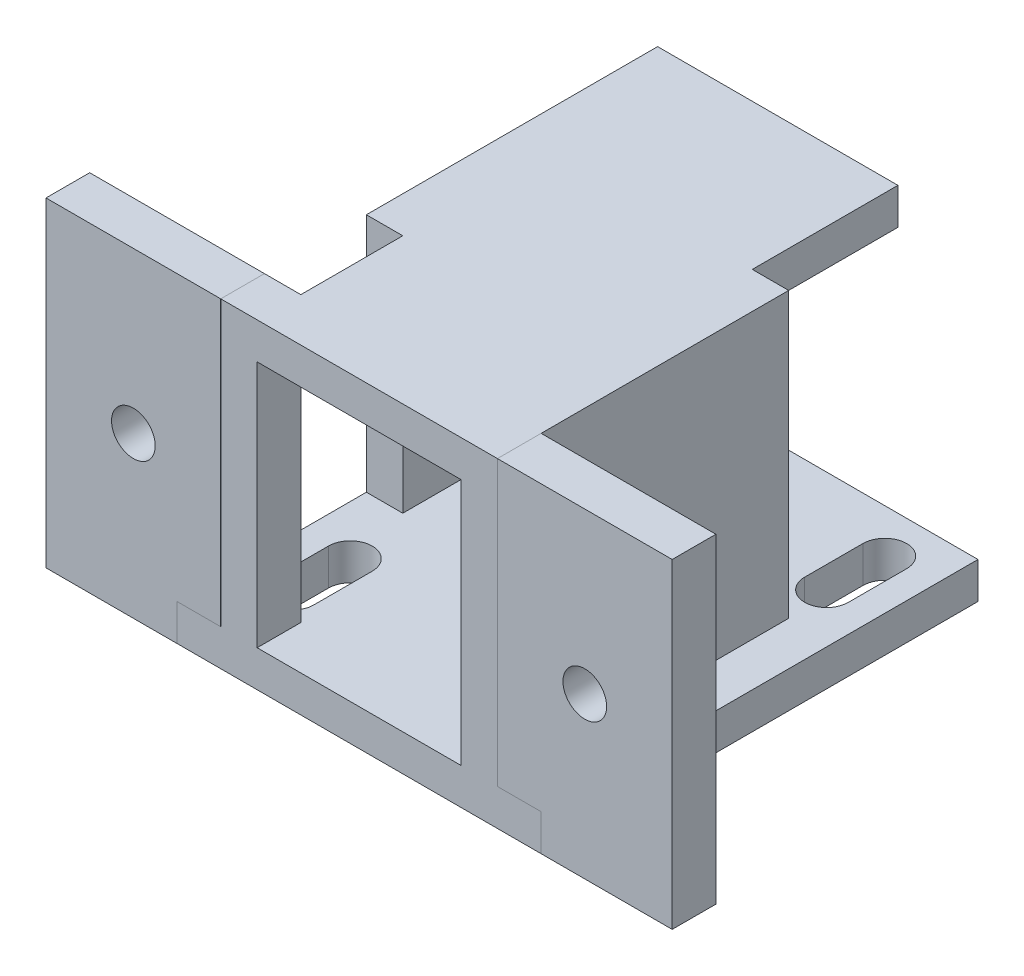
SolidWorks part; units mm, degrees
ref_plane "Front Plane" through (0, 0, 0) normal (0, 0, 1) x (1, 0, 0)
ref_plane "Top Plane" through (0, 0, 0) normal (0, 1, 0) x (1, 0, 0)
ref_plane "Right Plane" through (0, 0, 0) normal (1, 0, 0) x (0, 0, -1)
sketch "Sketch1" plane through (0, 0, 0) normal (0, 0, 1) x (1, 0, 0)
  line L0 (9.5, 11) -> (9.5, -11)
  line L1 (7, 8.5) -> (-7, 8.5)
  line L2 (7, 8.5) -> (7, -8.5)
  line L3 (7, -8.5) -> (-7, -8.5)
  line L4 (-7, 8.5) -> (-7, -8.5)
  line L5 (7, 8.5) -> (-7, -8.5) construction
  line L6 (7, -8.5) -> (-7, 8.5) construction
  line L7 (9.5, -11) -> (-9.5, -11)
  line L8 (-9.5, 11) -> (-9.5, -11)
  line L9 (9.5, 11) -> (-9.5, 11)
  line L11 (-9.5, -11) -> (-12.5, -11)
  line L12 (-9.5, -11) -> (-9.5, -8.5)
  line L13 (-9.5, -8.5) -> (-12.5, -8.5)
  line L14 (-12.5, -11) -> (-12.5, -8.5)
  line L15 (9.5, -11) -> (12.5, -11)
  line L16 (9.5, -11) -> (9.5, -8.5)
  line L17 (9.5, -8.5) -> (12.5, -8.5)
  line L18 (12.5, -11) -> (12.5, -8.5)
  point P0 (0, 0)
  dimension "D1" = 17
  dimension "D2" = 14
  dimension "D4" = 25
  dimension "D3" = 2.5
extrude "Boss-Extrude1" add sketch "Sketch1" along normal blind 30 contours L0 L9 L8 L7 L4 L1 L2 L3 | L14 L11 L8 L13 | L15 L18 L17 L0
sketch "Sketch2" plane through (-9.5, 0, 0) normal (-1, 0, 0) x (0, 0, 1)
  line L1 (27, -5.5) -> (0, -5.5)
  line L2 (27, -5.5) -> (27, -8.5)
  line L3 (27, -8.5) -> (0, -8.5)
  line L4 (0, -5.5) -> (0, -8.5)
  line L6 (30, 11) -> (30, -8.5) construction
  line L7 (30, 11) -> (0, 11) construction
  line L8 (27, -5.5) -> (20, -5.5)
  line L9 (27, -5.5) -> (27, 11)
  line L10 (27, 11) -> (20, 11)
  line L11 (20, -5.5) -> (20, 11)
  line M8 (30, 11) -> (0, 11)
  line M9 (0, 11) -> (0, -8.5)
  line M10 (0, -8.5) -> (30, -8.5)
  dimension "D1" = 3
  dimension "D2" = 3
  dimension "D3" = 7
extrude "Cut-Extrude1" cut sketch "Sketch2" against normal up to surface (2.5 mm away) contours L2 L1 M9 M10 | L11 L1 L9 M8 up to face at (-7, 0, 15)
sketch "Sketch3" plane through (9.5, 0, 0) normal (1, 0, 0) x (0, 0, -1)
  line L1 (-10, -5.5) -> (0, -5.5)
  line L2 (-10, -5.5) -> (-10, -8.5)
  line L3 (-10, -8.5) -> (0, -8.5)
  line L4 (0, -5.5) -> (0, -8.5)
  line L6 (-10, -5.5) -> (0, -5.5)
  line L7 (-10, -5.5) -> (-10, 11)
  line L8 (-10, 11) -> (0, 11)
  line L9 (0, -5.5) -> (0, 11)
  line M6 (0, 11) -> (-30, 11)
  line M9 (0, -8.5) -> (0, 11)
  line M11 (-30, -8.5) -> (0, -8.5)
  dimension "D1" = 10
extrude "Cut-Extrude2" cut sketch "Sketch3" against normal up to surface (2.5 mm away) contours L7 L1 M9 M6 | L1 L2 M11 M9 up to face at (7, 0, 15)
sketch "Sketch5" plane through (0, -8.5, 0) normal (0, 1, 0) x (1, 0, 0)
  line L0 (-9.1, -25.5) -> (-9.1, -21.5) construction
  line L1 (-10.6, -25.5) -> (-10.6, -21.5)
  line L2 (-7.6, -25.5) -> (-7.6, -21.5)
  line L3 (9.1, -7) -> (9.1, -3) construction
  line L4 (7.6, -7) -> (7.6, -3)
  line L5 (10.6, -7) -> (10.6, -3)
  line L7 (9.1, -5) -> (-9.1, -5) construction
  line L8 (-7, -27) -> (-7, -20) construction
  line L9 (7, -10) -> (7, 0) construction
  arc A2 (-10.6, -25.5) -> (-7.6, -25.5) centre (-9.1, -25.5) ccw
  arc A3 (-7.6, -21.5) -> (-10.6, -21.5) centre (-9.1, -21.5) ccw
  arc A4 (7.6, -7) -> (10.6, -7) centre (9.1, -7) ccw
  arc A5 (10.6, -3) -> (7.6, -3) centre (9.1, -3) ccw
  point P2 (-9.1, -23.5)
  point P7 (9.1, -5)
  point P15 (0, -5)
  point P24 (-7, -23.5)
  point P28 (7, -5)
  dimension "D2" = 4
  dimension "D4" = 1.5
  dimension "D1" = 18.2
extrude "Cut-Extrude3" cut sketch "Sketch5" against normal through all
sketch "Sketch6" plane through (0, 0, 30) normal (0, 0, 1) x (1, 0, 0)
  line L0 (-9.5, 11) -> (-9.5, -8.5) construction
  line L1 (-9.5, 11) -> (-21.5, 11)
  line L2 (-9.5, 11) -> (-9.5, -8.5)
  line L3 (-9.5, -8.5) -> (-21.5, -8.5)
  line L4 (-21.5, 11) -> (-21.5, -8.5)
  line L5 (9.5, 11) -> (9.5, -8.5) construction
  line L6 (9.5, 11) -> (21.5, 11)
  line L7 (9.5, 11) -> (9.5, -8.5)
  line L8 (9.5, -8.5) -> (21.5, -8.5)
  line L9 (21.5, 11) -> (21.5, -8.5)
  line L11 (-21.5, -8.5) -> (-12.5, -8.5)
  line L12 (-21.5, -8.5) -> (-21.5, -11)
  line L13 (-21.5, -11) -> (-12.5, -11)
  line L14 (-12.5, -8.5) -> (-12.5, -11)
  line L15 (21.5, -8.5) -> (12.5, -8.5)
  line L16 (21.5, -8.5) -> (21.5, -11)
  line L17 (21.5, -11) -> (12.5, -11)
  line L18 (12.5, -8.5) -> (12.5, -11)
  circle A0 centre (-15.5, 0) radius 1.5
  circle A1 centre (15.5, 0) radius 1.5
  point P22 (-15.5, 11)
  point P24 (15.5, 11)
  line M15 (9.5, -8.5) -> (9.5, 11)
  line M17 (-9.5, 11) -> (-9.5, -8.5)
  line M18 (-9.5, -8.5) -> (-12.5, -8.5)
  line M19 (-12.5, -8.5) -> (-12.5, -11)
  line M21 (12.5, -11) -> (12.5, -8.5)
  line M22 (12.5, -8.5) -> (9.5, -8.5)
  dimension "D1" = 3
  dimension "D2" = 31
extrude "Boss-Extrude2" add sketch "Sketch6" against normal blind 3 separate body contours L1 L4 L3 A0 M18 M17 | L12 L13 L3 M19 | L17 L16 L8 M21 | L9 L6 L8 A1 M15 M22
